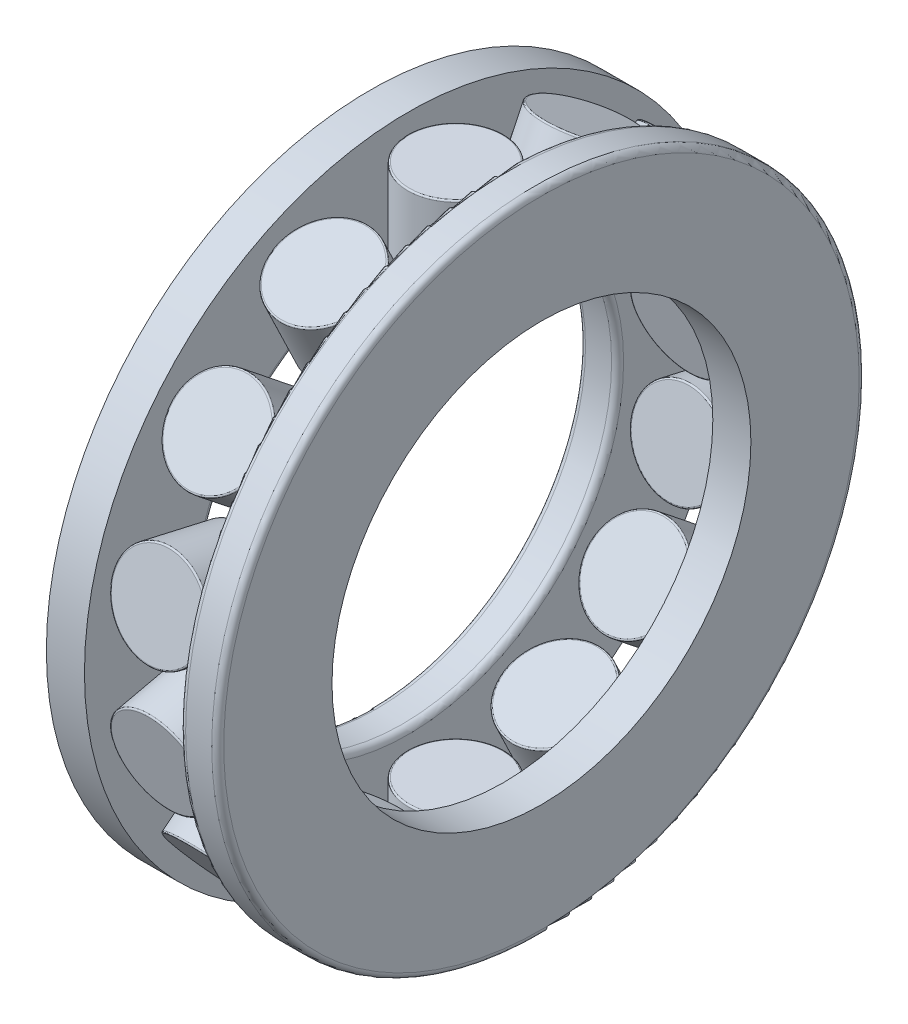
SolidWorks part; units mm, degrees
ref_plane "Plane1" through (0, 0, 0) normal (0, 0, 1) x (1, 0, 0)
ref_plane "Plane2" through (0, 0, 0) normal (0, 1, 0) x (1, 0, 0)
ref_plane "Plane3" through (0, 0, 0) normal (1, 0, 0) x (0, 0, -1)
sketch "Clipboard" plane through (0, 0, 0) normal (0, 0, 1) x (1, 0, 0)
  line L0 (-10, 0) -> (10, 0) construction
  line L1 (0, 0) -> (21.6965, -5.4095)
  line L2 (0, 0) -> (27.3662, 35.0271)
  line L3 (0, 0) -> (13.7666, -17.6205)
  line L4 (0, 0) -> (-22.3471, -0.7804)
  dimension "BallCLRad" = 44.45
  dimension "Count" = 52
  dimension "Show_count" = 52
  dimension "Max_count" = 14
  dimension "Min_count" = 2
sketch "InnRacSke" plane through (0, 0, 0) normal (0, 0, 1) x (1, 0, 0)
  line L1 (-7.9375, 34.925) -> (-14.2875, 34.925)
  line L2 (-14.2875, 34.925) -> (-14.2875, 53.975)
  line L3 (-14.2875, 53.975) -> (-7.9375, 53.975)
  line L4 (-7.9375, 53.975) -> (-7.9375, 34.925)
  line L5 (-34.925, 0) -> (34.925, 0) construction
  line L6 (0, 0) -> (0, 25.4) construction
  dimension "ID" = 69.85
  dimension "OD" = 107.95
  dimension "Width" = 28.575
  dimension "gap" = 15.875
revolve "Race" add sketch "InnRacSke" angle 360 about L5
ref_axis "Axis1" through (-50, 0, 0) along (1, 0, 0)
sketch "RolDetSke" plane through (0, 0, 0) normal (0, 0, 1) x (1, 0, 0)
  line L0 (0, 33.02) -> (0, 55.88) construction
  line L3 (0, 50.8) -> (7.7232, 50.8)
  line L4 (0, 50.8) -> (0, 38.1)
  line L5 (0, 38.1) -> (7.7232, 38.1)
  line L6 (7.9772, 50.546) -> (7.9772, 38.354)
  arc A0 (7.9772, 38.354) -> (7.7232, 38.1) centre (7.7232, 38.354) cw
  arc A1 (7.7232, 50.8) -> (7.9772, 50.546) centre (7.7232, 50.546) cw
  dimension "D1" = 0.254
  dimension "Roller_diameter" = 15.9544
  dimension "Cyl_Len" = 12.7
  dimension "offset" = 38.1
revolve "RollerDetailed" add sketch "RolDetSke" angle 360 about L0
sketch "RolSimSke" plane through (0, 0, 0) normal (0, 0, 1) x (1, 0, 0)
  line L1 (-17.78, 0) -> (12.7, 0) construction
  line L3 (-7.7232, 50.8) -> (7.7232, 50.8)
  line L4 (-7.9772, 50.546) -> (-7.9772, 38.354)
  line L5 (-7.7232, 38.1) -> (7.7232, 38.1)
  line L6 (7.9772, 50.546) -> (7.9772, 38.354)
  arc A0 (-7.9772, 38.354) -> (-7.7232, 38.1) centre (-7.7232, 38.354) ccw
  arc A1 (-7.7232, 50.8) -> (-7.9772, 50.546) centre (-7.7232, 50.546) ccw
  arc A2 (7.9772, 50.546) -> (7.7232, 50.8) centre (7.7232, 50.546) ccw
  arc A3 (7.7232, 38.1) -> (7.9772, 38.354) centre (7.7232, 38.354) ccw
  dimension "Roller_diameter" = 15.9544
  dimension "Cyl_Len" = 12.7
  dimension "offset" = 38.1
  dimension "Rol_rad" = 0.254
  dimension "Halfdia" = 7.9772
revolve "RollersSimplified" [suppressed] add sketch "RolSimSke" angle 360 about L1
mirror "Mirror1" about plane through (0, 0, 0) normal (1, 0, 0) of "Race"
fillet "Fillet" radius 1 4 edges at (7.9375, 0, -53.975) (14.2875, 0, -53.975) (-7.9375, 0, -34.925) (-14.2875, 0, -34.925)
pattern_circular "RollersDetailed" count 14 every 25.714 about axis through (-50, 0, 0) along (1, 0, 0) of "RollerDetailed"
sketch "CagSpiSke" plane through (0, 0, 0) normal (0, 0, 1) x (1, 0, 0)
  line L0 (2.3932, 35.6235) -> (2.3932, 52.8955)
  line L1 (2.3932, 52.8955) -> (-2.3932, 52.8955)
  line L2 (-2.3932, 35.6235) -> (-2.3932, 52.8955)
  line L3 (-2.3932, 35.6235) -> (2.3932, 35.6235)
  line L4 (-34.925, 0) -> (34.925, 0) construction
  line L5 (0, 0) -> (0, 63.1161) construction
  dimension "ID" = 71.247
  dimension "OD" = 105.791
  dimension "Thickness" = 4.7863
revolve "CageSpine" [suppressed] add sketch "CagSpiSke" angle 360 about L4
equation "\"BallCLRad@Clipboard\" =  ( \"OD@InnRacSke\" + \"ID@InnRacSke\" )  / 4"
equation "\"offset@RolDetSke\" = \"BallCLRad@Clipboard\" - \"Cyl_Len@RolDetSke\" / 2"
equation "\"Cyl_Len@RolSimSke\" = \"Cyl_Len@RolDetSke\""
equation "\"offset@RolSimSke\" = \"BallCLRad@Clipboard\" - \"Cyl_Len@RolSimSke\" / 2"
equation "\"Roller_diameter@RolDetSke\" = \"gap@InnRacSke\" * 1.005"
equation "\"Roller_diameter@RolSimSke\" = \"gap@InnRacSke\" * 1.005"
equation "\"Max_count@Clipboard\" = int( 3.14159265 / atn(( \"Roller_diameter@RolDetSke\" / 2) / sqr( \"offset@RolDetSke\"  *  \"offset@RolDetSke\" - ( \"Roller_diameter@RolDetSke\" / 2) *  ( \"Roller_diameter@RolDetSke\" / 2))))"
equation "\"Max_count@Clipboard\" = ((sgn( \"Max_count@Clipboard\" - \"Count@Clipboard\" )-1)*( \"Max_count@Clipboard\" - \"Count@Clipboard\" ))/-2+ \"Count@Clipboard\""
equation "\"Count@RollersDetailed\" = int( \"Show_count@Clipboard\" ) "
equation "\"Count@RollersDetailed\" = ((sgn( \"Count@RollersDetailed\" - \"Max_count@Clipboard\" )-1)*( \"Count@RollersDetailed\" - \"Max_count@Clipboard\" ))/-2+ \"Max_count@Clipboard\""
equation "\"Count@RollersDetailed\" = ((sgn( \"Count@RollersDetailed\" - \"Min_count@Clipboard\" )+1)*( \"Count@RollersDetailed\" - \"Min_count@Clipboard\"))/2 +\"Min_count@Clipboard\""
equation "\"Angle@RollersDetailed\" = 360.0 / \"Max_count@Clipboard\""
equation "\"Angle@CageSpine\" =  \"Angle@RollersDetailed\" * ( \"Count@RollersDetailed\" -1 + int( \"Count@RollersDetailed\" / \"Max_count@Clipboard\" ) )  + 0.001 -  int( \"Count@RollersDetailed\" / \"Max_count@Clipboard\" ) * 0.001"
equation "\"Angle@CageSpine\" =  \"Angle@CageSpine\" * int( \"Min_count@Clipboard\" / 2) + int(1 / \"Min_count@Clipboard\")  * 0.001"
equation "\"Thickness@CagSpiSke\" =  \"Roller_diameter@RolDetSke\" * 0.3"
equation "\"OD@CagSpiSke\" = \"OD@InnRacSke\" * 0.98"
equation "\"ID@CagSpiSke\" =  \"ID@InnRacSke\" * 1.02"
equation "\"Halfdia@RolSimSke\" = \"Roller_diameter@RolSimSke\" / 2"
